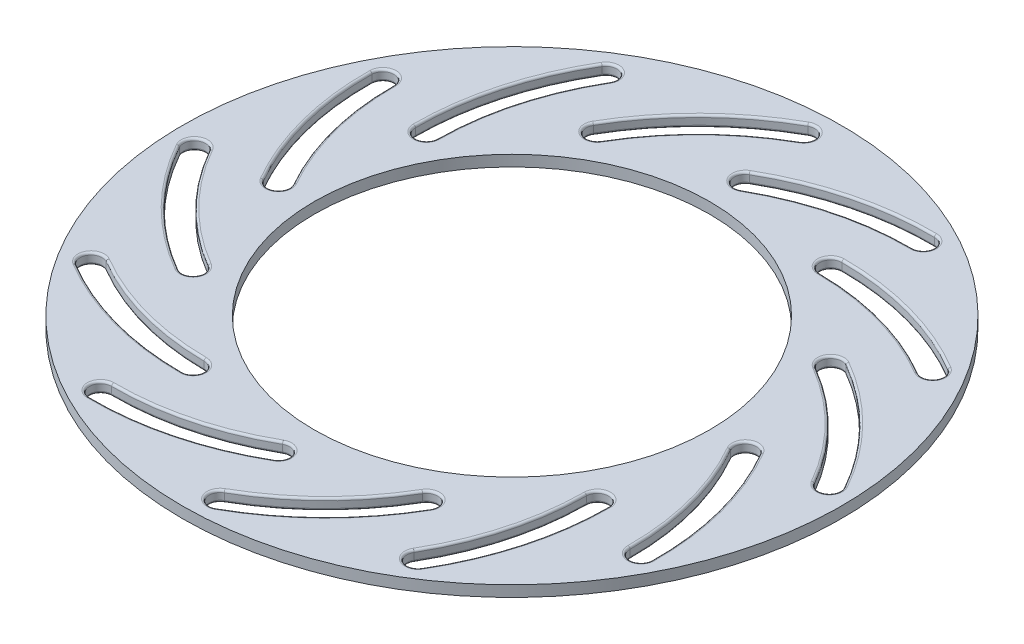
SolidWorks part; units mm, degrees
ref_plane "Front Plane" through (0, 0, 0) normal (0, 0, 1) x (1, 0, 0)
ref_plane "Top Plane" through (0, 0, 0) normal (0, 1, 0) x (1, 0, 0)
ref_plane "Right Plane" through (0, 0, 0) normal (1, 0, 0) x (0, 0, -1)
sketch "sketch 01" plane through (0, 0, 0) normal (0, 1, 0) x (1, 0, 0)
  circle A0 centre (0, 0) radius 36
  circle A1 centre (0, 0) radius 60
  dimension "D1" = 120
  dimension "D2" = 72
extrude "top ring" add sketch "sketch 01" along normal blind 2
sketch "Sketch2" plane through (0, 2, 0) normal (0, 1, 0) x (1, 0, 0)
  line L0 (0, 0) -> (0, 72.7751) construction
  line L1 (0, 42.5) -> (27.0676, 58.1275) construction
  circle A0 centre (0, 0) radius 55.5 construction
  circle A1 centre (0, 0) radius 42.5 construction
  arc A2 (-1, 44.2321) -> (25.7223, 51.1937) centre (25, -0.8013) cw
  arc A3 (0.9908, 40.7627) -> (25.6774, 47.194) centre (25.2566, -1.7863) cw
  circle A4 centre (25, -0.8013) radius 50 construction
  arc A5 (25.7223, 51.1937) -> (25.6774, 47.194) centre (25.6945, 49.1939) cw
  arc A6 (-1, 44.2321) -> (0.9908, 40.7627) centre (0, 42.5) ccw
  point P19 (0, 42.5)
  dimension "D1" = 85
  dimension "D2" = 111
  dimension "D3" = 100
  dimension "D4" = 60
  dimension "D5" = 2
extrude "Cut-Extrude1" cut sketch "Sketch2" against normal through all contours A3 A5 A2 A6
fillet "Fillet1" radius 0.4 8 edges at (12.908, 0, -45.6137) (27.6944, 0, -49.1714) (27.6944, 2, -49.1714) (-1.7347, 0, -41.5046) (-1.7347, 2, -41.5046) (12.908, 2, -45.6137) (11.8906, 0, -49.5191) (11.8906, 2, -49.5191)
pattern_circular "CirPattern1" count 12 over 360 about axis through (0, 0, 0) along (0, 1, 0) of "Cut-Extrude1", "Fillet1"
equation "\"D1@CirPattern1\"=\"grooves@Shutter Assembly.Assembly\""
